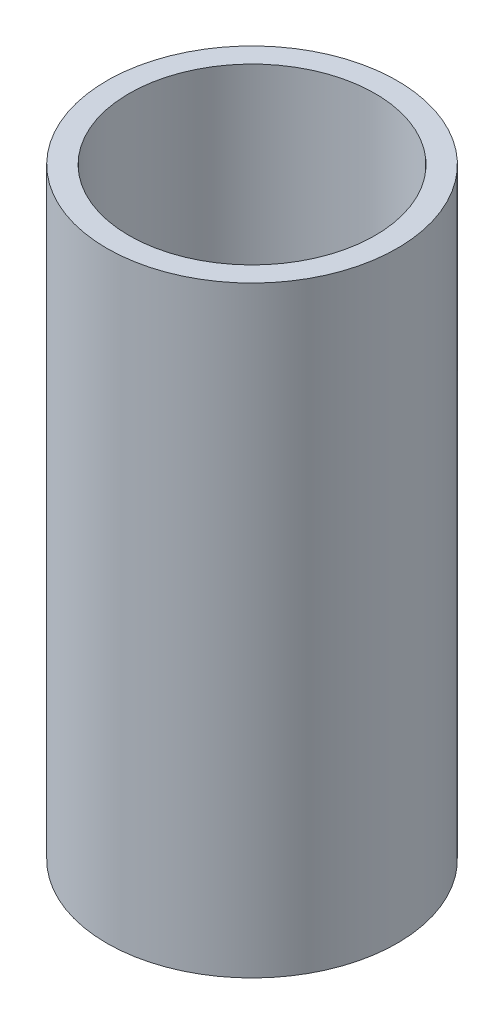
SolidWorks part; units mm, degrees
ref_plane "Front Plane" through (0, 0, 0) normal (0, 0, 1) x (1, 0, 0)
ref_plane "Top Plane" through (0, 0, 0) normal (0, 1, 0) x (1, 0, 0)
ref_plane "Right Plane" through (0, 0, 0) normal (1, 0, 0) x (0, 0, -1)
sketch "Sketch1" plane through (0, 0, 0) normal (0, 1, 0) x (1, 0, 0)
  circle A0 centre (0, 0) radius 24.13
  circle A1 centre (0, 0) radius 20.445
  dimension "Diametro exterior" = 48.26
  dimension "Diametro interior" = 40.89
extrude "Boss-Extrude1" add sketch "Sketch1" along normal blind 100
